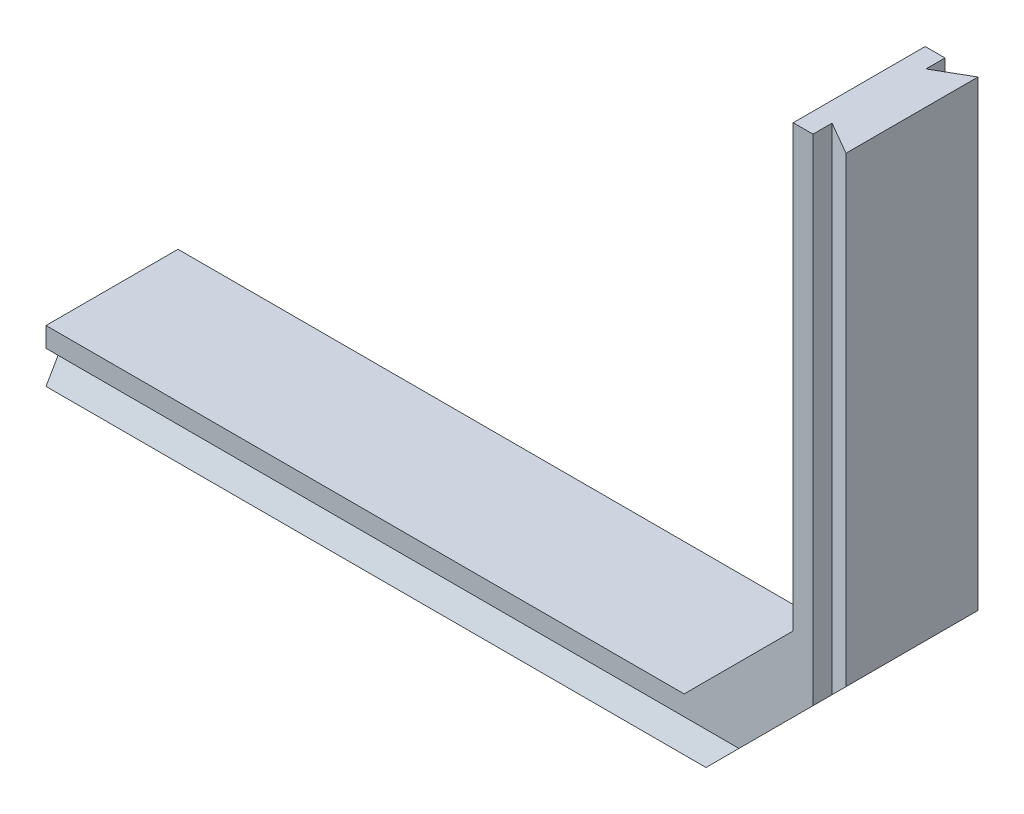
SolidWorks part; units mm, degrees
ref_plane "Спереди" through (0, 0, 0) normal (0, 0, 1) x (1, 0, 0)
ref_plane "Сверху" through (0, 0, 0) normal (0, 1, 0) x (1, 0, 0)
ref_plane "Справа" through (0, 0, 0) normal (1, 0, 0) x (0, 0, -1)
sketch "Эскиз1" plane through (0, 0, 0) normal (0, 0, 1) x (1, 0, 0)
  line L0 (0, 0) -> (0, -8)
  line L1 (0, -8) -> (100, -8)
  line L2 (100, -8) -> (121.2132, 13.2132)
  line L3 (121.2132, 13.2132) -> (121.2132, 83.2132)
  line L4 (121.2132, 83.2132) -> (113.2132, 83.2132)
  line L5 (113.2132, 83.2132) -> (113.2132, 16.5269)
  line L6 (113.2132, 16.5269) -> (96.6863, 0)
  line L7 (96.6863, 0) -> (0, 0)
  dimension "D1" = 100
  dimension "D2" = 135
  dimension "D3" = 8
  dimension "D4" = 8
  dimension "D5" = 70
  dimension "D6" = 8
  dimension "D7" = 30
extrude "Бобышка-Вытянуть1" add sketch "Эскиз1" along normal blind 20
sketch "Эскиз2" plane through (0, 0, 0) normal (-1, 0, 0) x (0, 0, 1)
  line L0 (0, -3) -> (2.8868, -3)
  line L2 (20, -8) -> (0, -8) construction
  line L3 (0, 0) -> (0, -8) construction
  line L4 (2.8868, -3) -> (0, -8)
  line L5 (0, -8) -> (0, -3)
  line L7 (20, -8) -> (20, -3)
  line L8 (20, -3) -> (17.1132, -3)
  line L9 (10, -8) -> (10, -2.4441) construction
  line L10 (17.1132, -3) -> (20, -8)
  dimension "D1" = 60
  dimension "D2" = 5
extrude "Вырез-Вытянуть1" cut sketch "Эскиз2" against normal through all
sketch "Эскиз3" plane through (0, 83.2132, 0) normal (0, 1, 0) x (1, 0, 0)
  line L0 (116.2132, -20) -> (116.2132, -17.1132)
  line L1 (121.2132, -20) -> (113.2132, -20) construction
  line L2 (116.2132, -17.1132) -> (121.2132, -20)
  line L3 (121.2132, -20) -> (116.2132, -20)
  line L4 (121.2132, -10) -> (115.5253, -10) construction
  line L5 (121.2132, -20) -> (121.2132, 0) construction
  line L6 (121.2132, 0) -> (116.2132, 0)
  line L7 (116.2132, 0) -> (116.2132, -2.8868)
  line L8 (116.2132, -2.8868) -> (121.2132, 0)
  dimension "D1" = 5
  dimension "D2" = 60
extrude "Вырез-Вытянуть2" cut sketch "Эскиз3" against normal through all
sketch "Эскиз4" [suppressed] plane through (0, 0, 0) normal (-1, 0, 0) x (0, 0, 1)
  line L0 (0, -8) -> (2.3094, -4)
  line L1 (2.3094, -4) -> (17.6906, -4)
  line L2 (17.6906, -4) -> (20, -8)
  line L3 (20, -8) -> (0, -8)
  dimension "D1" = 4
  dimension "D2" = 60
  dimension "D3" = 60
